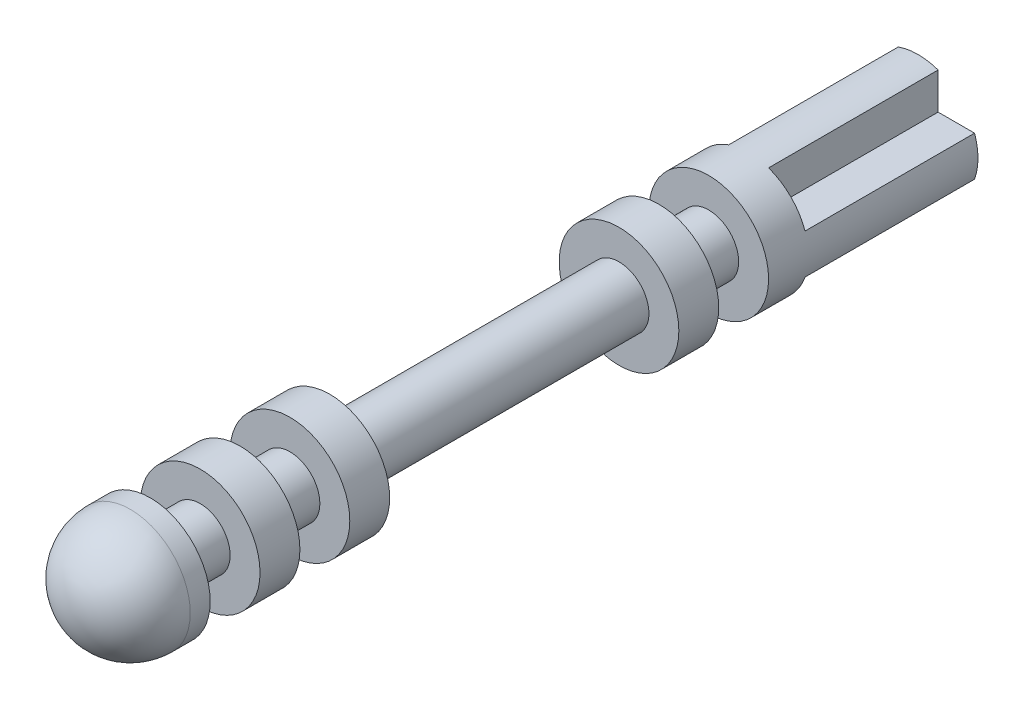
SolidWorks part; units mm, degrees
ref_plane "前视基准面" through (0, 0, 0) normal (0, 0, 1) x (1, 0, 0)
ref_plane "上视基准面" through (0, 0, 0) normal (0, 1, 0) x (1, 0, 0)
ref_plane "右视基准面" through (0, 0, 0) normal (1, 0, 0) x (0, 0, -1)
sketch "草图1" plane through (0, 0, 0) normal (0, 0, 1) x (1, 0, 0)
  circle A0 centre (0, 0) radius 3
  dimension "D1" = 6
extrude "凸台-拉伸1" add sketch "草图1" along normal blind 10.5
sketch "草图3" plane through (0, 0, 0) normal (0, 0, 1) x (1, 0, 0)
  circle A0 centre (0, 0) radius 1.5
  dimension "D1" = 3
extrude "凸台-拉伸2" add sketch "草图3" along normal blind 13
sketch "草图4" plane through (0, 0, 13) normal (0, 0, 1) x (1, 0, 0)
  circle A0 centre (0, 0) radius 3
  dimension "D1" = 6
extrude "凸台-拉伸3" add sketch "草图4" along normal blind 2
sketch "草图5" plane through (0, 0, 0) normal (0, 0, 1) x (1, 0, 0)
  circle A0 centre (0, 0) radius 1.5
  dimension "D1" = 3
extrude "凸台-拉伸4" add sketch "草图5" along normal blind 38.5
sketch "草图7" plane through (0, 0, 0) normal (0, 0, 1) x (1, 0, 0)
  circle A0 centre (0, 0) radius 3 construction
  circle A1 centre (0, 0) radius 3
extrude "凸台-拉伸5" add sketch "草图7" along normal blind 2 from offset 29.5
sketch "草图8" plane through (0, 0, 0) normal (0, 0, 1) x (1, 0, 0)
  circle A1 centre (0, 0) radius 3
  circle A2 centre (0, 0) radius 3
  dimension "D1" = 0
extrude "凸台-拉伸6" add sketch "草图8" along normal blind 2 from offset 34
sketch "草图9" plane through (0, 0, 38.5) normal (0, 0, 1) x (1, 0, 0)
  circle A0 centre (0, 0) radius 3
  dimension "D1" = 6
extrude "凸台-拉伸7" add sketch "草图9" along normal blind 4
fillet "圆角1" radius 3 1 edges at (3, 0, 42.5)
sketch "草图10" plane through (0, 0, 0) normal (0, 0, -1) x (-1, 0, 0)
  line L0 (-2.8284, 1) -> (-1, 1)
  line L1 (-1, 1) -> (-1, 2.8284)
  line L2 (0, 3.3) -> (0, -3.3) construction
  circle A0 centre (0, 0) radius 3 construction
  dimension "D1" = 1
extrude "切除-拉伸1" cut sketch "草图10" against normal blind 8.5 and the other way through all
mirror "镜向2" about plane through (0, 0, 0) normal (0, 1, 0) of "切除-拉伸1" second plane through (0, 0, 0) second plane normal (1, 0, 0)
